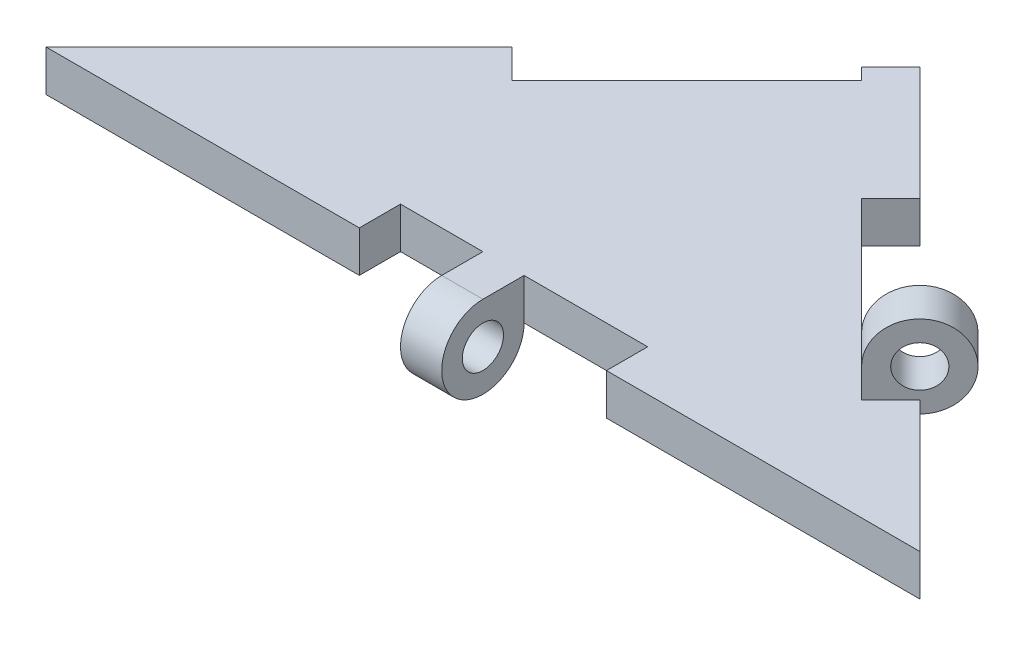
SolidWorks part; units mm, degrees
material "PET"
ref_plane "Front Plane" through (0, 0, 0) normal (0, 0, 1) x (1, 0, 0)
ref_plane "Top Plane" through (0, 0, 0) normal (0, 1, 0) x (1, 0, 0)
ref_plane "Right Plane" through (0, 0, 0) normal (1, 0, 0) x (0, 0, -1)
other "Center of Mass"
sketch "Sketch1" plane through (0, 0, 0) normal (0, 1, 0) x (1, 0, 0)
  line L0 (-53.033, 0) -> (53.033, 0)
  line L1 (-53.033, 0) -> (0, 53.033)
  line L2 (0, 53.033) -> (53.033, 0)
  dimension "D1" = 75
extrude "Boss-Extrude1" add sketch "Sketch1" along normal blind 5
sketch "Sketch2" plane through (0, 5, 0) normal (0, 1, 0) x (1, 0, 0)
  line L0 (-15, 0) -> (15, 0)
  line L1 (-15, 0) -> (-15, 5)
  line L2 (15, 0) -> (15, 5)
  line L3 (-15, 5) -> (15, 5)
  line L4 (-53.033, 0) -> (53.033, 0) construction
  line L5 (0, 0) -> (0, 8.7982) construction
  line L6 (-3.5355, 49.4975) -> (-24.7487, 28.2843)
  line L7 (-3.5355, 49.4975) -> (0, 45.9619)
  line L8 (-24.7487, 28.2843) -> (-21.2132, 24.7487)
  line L9 (0, 45.9619) -> (-21.2132, 24.7487)
  line L10 (0, 53.033) -> (-53.033, 0) construction
  line L11 (53.033, 0) -> (0, 53.033) construction
  dimension "D1" = 5
  dimension "D2" = 30
  dimension "D3" = 5
  dimension "D4" = 30
  dimension "D5" = 35
extrude "Cut-Extrude1" cut sketch "Sketch2" against normal blind 5
sketch "Sketch3" plane through (0, 0, 0) normal (0, -1, 0) x (1, 0, 0)
  line L0 (15.9099, -37.1231) -> (37.1231, -15.9099)
  line L1 (15.9099, -37.1231) -> (12.3744, -33.5876)
  line L2 (37.1231, -15.9099) -> (33.5876, -12.3744)
  line L3 (12.3744, -33.5876) -> (33.5876, -12.3744)
  line L4 (53.033, 0) -> (0, -53.033) construction
  line L5 (26.5165, -26.5165) -> (16.2125, -16.2125) construction
  dimension "D1" = 5
  dimension "D2" = 30
extrude "Cut-Extrude2" cut sketch "Sketch3" against normal blind 5
sketch "Sketch5" plane through (15, 0, 0) normal (-1, 0, 0) x (0, 0, 1)
  circle A0 centre (0, 0) radius 5
  circle A1 centre (0, 0) radius 2.5
  dimension "D1" = 5
extrude "Boss-Extrude2" add sketch "Sketch5" along normal blind 5 from offset 15
sketch "Sketch6" plane through (10.6066, 0, 10.6066) normal (-0.7071, 0, -0.7071) x (-0.7071, 0, 0.7071)
  circle A0 centre (-37.5, 5) radius 5
  circle A1 centre (-37.5, 5) radius 2.5
  dimension "D1" = 5
extrude "Boss-Extrude3" add sketch "Sketch6" along normal blind 5 from offset 5
sketch "Sketch7" plane through (0, 5, 0) normal (0, 1, 0) x (1, 0, 0)
  line L0 (0, 53.033) -> (-19.0381, 33.9949)
  line L1 (0, 53.033) -> (2.1213, 50.9117)
  line L2 (-19.0381, 33.9949) -> (-16.9168, 31.8736)
  line L3 (2.1213, 50.9117) -> (-16.9168, 31.8736)
  dimension "D1" = 3
extrude "Cut-Extrude3" cut sketch "Sketch7" against normal blind 10
chamfer "Chamfer1" [suppressed] distance 2 angle 45
other "Center of Mass Reference Point1"
